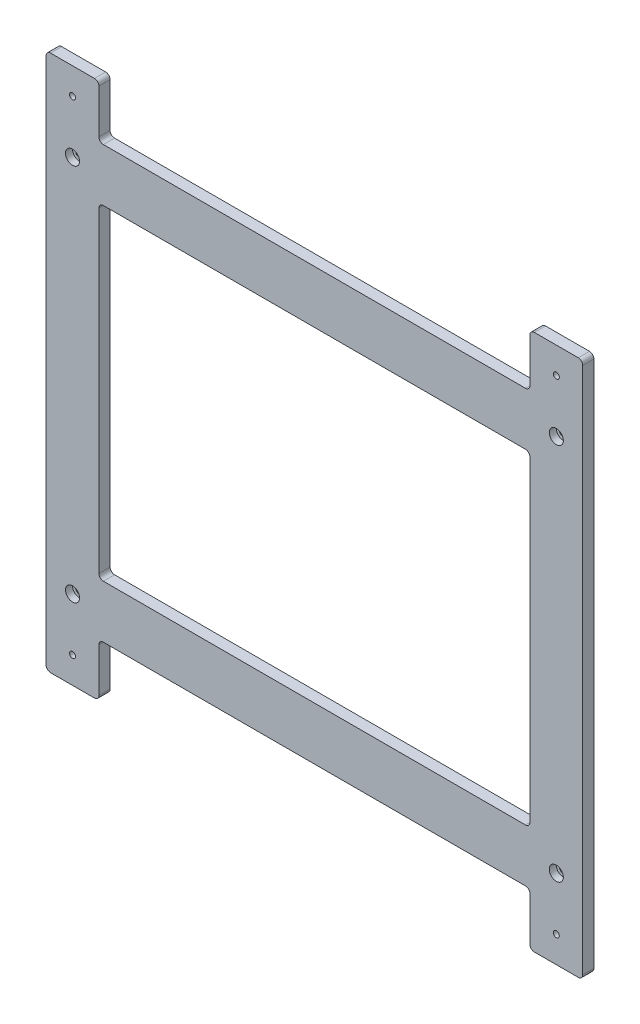
SolidWorks part; units mm, degrees
ref_plane "Front Plane" through (0, 0, 0) normal (0, 0, 1) x (1, 0, 0)
ref_plane "Top Plane" through (0, 0, 0) normal (0, 1, 0) x (1, 0, 0)
ref_plane "Right Plane" through (0, 0, 0) normal (1, 0, 0) x (0, 0, -1)
sketch "Sketch7" plane through (0, 0, 0) normal (0, 0, 1) x (1, 0, 0)
  line L1 (-119.9, -92.4) -> (119.9, -92.4)
  line L2 (-122.4, -89.9) -> (-122.4, 89.9)
  line L3 (-119.9, 92.4) -> (119.9, 92.4)
  line L4 (122.4, -89.9) -> (122.4, 89.9)
  line L5 (-122.4, -92.4) -> (122.4, 92.4) construction
  line L6 (-122.4, 92.4) -> (122.4, -92.4) construction
  line L7 (-119.9, -122.4) -> (119.9, -122.4)
  line L8 (-152.4, -120.7432) -> (-152.4, 102.187)
  line L9 (-119.9, 122.4) -> (119.9, 122.4)
  line L10 (152.4, -102.187) -> (152.4, 120.7432)
  line L11 (-152.4, -120.7432) -> (152.4, 120.7432) construction
  line L12 (-152.4, 102.187) -> (152.4, -102.187) construction
  line L14 (-152.4, 102.187) -> (-152.4, 149.9)
  line L15 (-149.9, 152.4) -> (-124.9, 152.4)
  line L16 (-122.4, 124.9) -> (-122.4, 149.9)
  line L18 (122.4, 124.9) -> (122.4, 149.9)
  line L19 (124.9, 152.4) -> (149.9, 152.4)
  line L20 (152.4, 120.7432) -> (152.4, 149.9)
  line L22 (-152.4, -120.7432) -> (-152.4, -149.9)
  line L23 (-149.9, -152.4) -> (-124.9, -152.4)
  line L24 (-122.4, -124.9) -> (-122.4, -149.9)
  line L26 (152.4, -102.187) -> (152.4, -149.9)
  line L27 (149.9, -152.4) -> (124.9, -152.4)
  line L28 (122.4, -124.9) -> (122.4, -149.9)
  arc A0 (119.9, 92.4) -> (122.4, 89.9) centre (119.9, 89.9) cw
  arc A1 (119.9, -92.4) -> (122.4, -89.9) centre (119.9, -89.9) ccw
  arc A2 (-119.9, -92.4) -> (-122.4, -89.9) centre (-119.9, -89.9) cw
  arc A3 (-122.4, 89.9) -> (-119.9, 92.4) centre (-119.9, 89.9) cw
  arc A4 (-152.4, -149.9) -> (-149.9, -152.4) centre (-149.9, -149.9) ccw
  arc A5 (-124.9, -152.4) -> (-122.4, -149.9) centre (-124.9, -149.9) ccw
  arc A6 (-119.9, -122.4) -> (-122.4, -124.9) centre (-119.9, -124.9) ccw
  arc A7 (119.9, -122.4) -> (122.4, -124.9) centre (119.9, -124.9) cw
  arc A8 (124.9, -152.4) -> (122.4, -149.9) centre (124.9, -149.9) cw
  arc A9 (152.4, -149.9) -> (149.9, -152.4) centre (149.9, -149.9) cw
  arc A10 (149.9, 152.4) -> (152.4, 149.9) centre (149.9, 149.9) cw
  arc A11 (122.4, 149.9) -> (124.9, 152.4) centre (124.9, 149.9) cw
  arc A12 (119.9, 122.4) -> (122.4, 124.9) centre (119.9, 124.9) ccw
  arc A13 (-119.9, 122.4) -> (-122.4, 124.9) centre (-119.9, 124.9) cw
  arc A14 (-124.9, 152.4) -> (-122.4, 149.9) centre (-124.9, 149.9) cw
  arc A15 (-152.4, 149.9) -> (-149.9, 152.4) centre (-149.9, 149.9) cw
  point P0 (0, 0)
  point P6 (0, 0)
  point P37 (-152.4, -152.4)
  point P40 (-122.4, -152.4)
  point P43 (-122.4, -122.4)
  point P46 (122.4, -122.4)
  point P49 (122.4, -152.4)
  point P56 (122.4, 152.4)
  point P59 (122.4, 122.4)
  point P62 (-122.4, 122.4)
  point P65 (-122.4, 152.4)
  dimension "D15" = 2.5
  dimension "D1" = 304.8
  dimension "D2" = 304.8
  dimension "D3" = 30
  dimension "D4" = 30
  dimension "D5" = 30
  dimension "D6" = 30
  dimension "D7" = 30
  dimension "D8" = 30
  dimension "D9" = 30
  dimension "D10" = 30
  dimension "D11" = 30
  dimension "D12" = 30
  dimension "D13" = 30
  dimension "D14" = 30
extrude "Boss-Extrude1" add sketch "Sketch7" along normal blind 6.35
hole_wizard "CBORE for M4 SHCS1" positions "Sketch8" profile "Sketch9" counterbore size "M4" standard "ANSI Metric" end condition up to next
sketch "Sketch8" plane through (0, 0, 6.35) normal (0, 0, 1) x (1, 0, 0)
  line L0 (152.4, -149.9) -> (152.4, 149.9) construction
  line L1 (-152.4, 149.9) -> (-152.4, -149.9) construction
  line L2 (-119.9, -122.4) -> (119.9, -122.4) construction
  line L3 (119.9, 92.4) -> (-119.9, 92.4) construction
  point P0 (-137.4, 107.4)
  point P2 (-137.4, -107.4)
  point P4 (137.4, -107.4)
  point P6 (137.4, 107.4)
  point P9 (0, 0)
  point P10 (0, 0)
  point P11 (0, 0)
  dimension "D1" = 15
  dimension "D2" = 15
  dimension "D3" = 15
  dimension "D4" = 15
sketch "Sketch9" plane through (-137.4, 107.4, 6.35) normal (1, 0, 0) x (0, -1, 0)
  line L0 (0, 0) -> (0, 6.35)
  line L1 (0, 6.35) -> (2.25, 6.35)
  line L3 (2.25, 6.35) -> (2.25, 4)
  line L4 (2.25, 4) -> (4, 4)
  line L5 (4, 4) -> (4, 0)
  line L7 (4, 0) -> (0, 0)
  line L11 (0, -6.35) -> (0, 107.95) construction
  dimension "Thru Hole Dia." = 4.5
  dimension "Thru Hole Depth" = 6.35
  dimension "C'Bore Dia." = 8
  dimension "C'Bore Depth" = 4
hole_wizard "M3 Clearance Hole2" positions "Sketch10" profile "Sketch11" hole size "M3" standard "ANSI Metric" end condition up to next
sketch "Sketch10" plane through (0, 0, 6.35) normal (0, 0, 1) x (1, 0, 0)
  line L0 (152.4, -149.9) -> (152.4, 149.9) construction
  line L1 (149.9, 152.4) -> (124.9, 152.4) construction
  line L2 (-152.4, 149.9) -> (-152.4, -149.9) construction
  line L3 (-149.9, -152.4) -> (-124.9, -152.4) construction
  point P0 (-137.4, 137.4)
  point P2 (137.4, 137.4)
  point P4 (137.4, -137.4)
  point P6 (-137.4, -137.4)
  point P21 (-130.9447, 137.4)
  point P22 (0, 0)
  dimension "D1" = 15
  dimension "D2" = 15
  dimension "D3" = 15
  dimension "D4" = 15
sketch "Sketch11" plane through (-137.4, 137.4, 6.35) normal (1, 0, 0) x (0, -1, 0)
  line L0 (0, 0) -> (0, 6.35)
  line L1 (0, 6.35) -> (1.7, 6.35)
  line L2 (1.7, 6.35) -> (1.7, 0)
  line L5 (1.7, 0) -> (0, 0)
  line L11 (0, -6.35) -> (0, 107.95) construction
  dimension "Thru Hole Dia." = 3.4
  dimension "Thru Hole Depth" = 6.35
